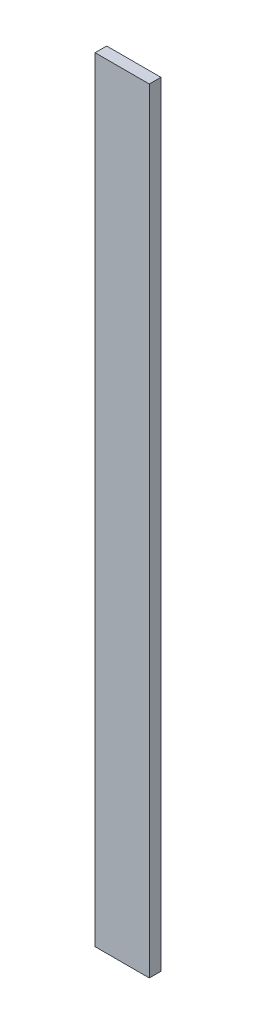
SolidWorks part; units mm, degrees
ref_plane "Front Plane" through (0, 0, 0) normal (0, 0, 1) x (1, 0, 0)
ref_plane "Top Plane" through (0, 0, 0) normal (0, 1, 0) x (1, 0, 0)
ref_plane "Right Plane" through (0, 0, 0) normal (1, 0, 0) x (0, 0, -1)
sketch "Sketch3" plane through (0, 0, 0) normal (0, 0, 1) x (1, 0, 0)
  line L1 (0, 0) -> (-70, 0)
  line L2 (0, 0) -> (0, -1000)
  line L3 (0, -1000) -> (-70, -1000)
  line L4 (-70, 0) -> (-70, -1000)
  dimension "D1" = 70
  dimension "D2" = 1000
extrude "Boss-Extrude1" add sketch "Sketch3" along normal blind 15 contours L2 L3 L4 L1
sketch "Sketch4" plane through (0, 0, 0) normal (0, 0, -1) x (-1, 0, 0)
  line L0 (0, 0) -> (70, 0) construction
  line L1 (70, 0) -> (70, -1000) construction
  circle A0 centre (35, -30) radius 10
  circle A13 centre (35, -180) radius 10
  circle A14 centre (35, -330) radius 10
  circle A15 centre (35, -480) radius 10
  circle A16 centre (35, -630) radius 10
  circle A17 centre (35, -780) radius 10
  circle A18 centre (35, -930) radius 10
  dimension "D1" = 20
  dimension "D5" = 150
  dimension "D2" = 30
  dimension "D3" = 35
  dimension "D4" = 7
extrude "Cut-Extrude1" cut sketch "Sketch4" against normal blind 8 contours A0 | A13 | A14 | A15 | A16 | A17 | A18
